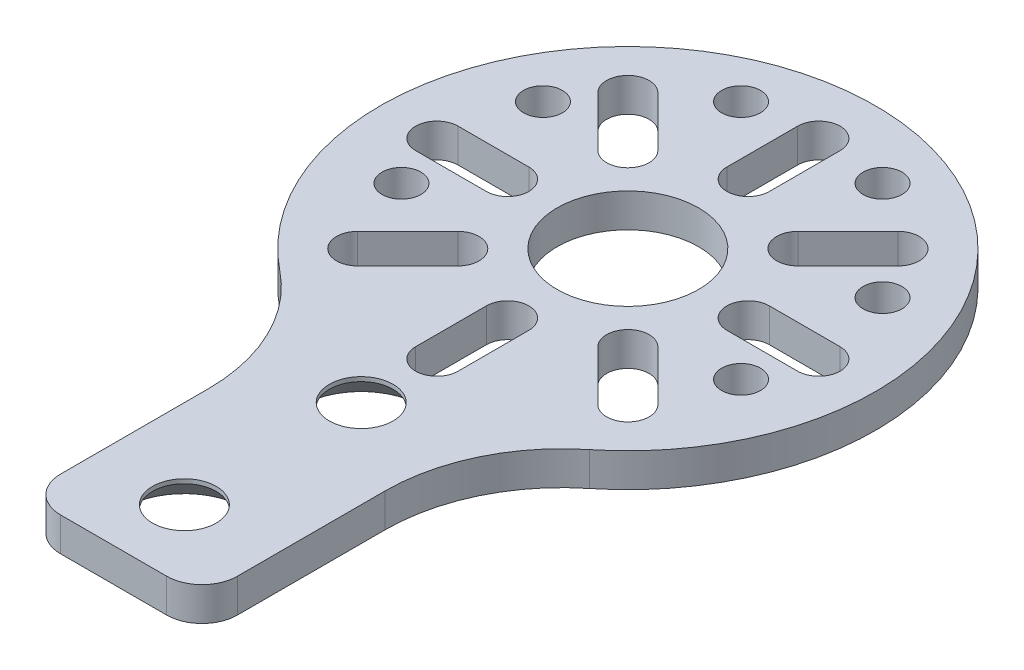
SolidWorks part; units mm, degrees
material "1060 Alloy"
ref_plane "Front Plane" through (0, 0, 0) normal (0, 0, 1) x (1, 0, 0)
ref_plane "Top Plane" through (0, 0, 0) normal (0, 1, 0) x (1, 0, 0)
ref_plane "Right Plane" through (0, 0, 0) normal (1, 0, 0) x (0, 0, -1)
sketch "Sketch1" plane through (0, 0, 0) normal (0, 1, 0) x (1, 0, 0)
  line L0 (-12.5, -72.6917) -> (12.5, -72.6917)
  line L1 (12.5, -72.6917) -> (12.5, -32.6917)
  line L2 (-12.5, -72.6917) -> (-12.5, -32.6917)
  arc A0 (12.5, -32.6917) -> (-12.5, -32.6917) centre (0, 0) ccw
  point P5 (0, -72.6917)
  dimension "D2" = 70
  dimension "D1" = 25
  dimension "D3" = 40
extrude "Boss-Extrude1" add sketch "Sketch1" along normal blind 4.7625 contours A0 L2 L0 L1
sketch "Sketch2" plane through (0, 0, 0) normal (0, -1, 0) x (1, 0, 0)
  line L0 (0, -2.6194) -> (0, 2.6194) construction
  point P0 (-10, -26)
  point P1 (-24, -12)
  point P4 (-24, 8)
  point P15 (24, 8)
  point P17 (24, -12)
  point P18 (10, -26)
  dimension "D2" = 26
  dimension "D1" = 8
  dimension "D3" = 10
  dimension "D4" = 24
  dimension "D5" = 20
sketch "Sketch5" plane through (0, 0, 0) normal (0, -1, 0) x (1, 0, 0)
  circle A0 centre (0, 0) radius 10
  dimension "D1" = 20
extrude "Cut-Extrude1" cut sketch "Sketch5" against normal through all
sketch "Sketch6" plane through (0, 0, 0) normal (0, -1, 0) x (1, 0, 0)
  line L0 (0, 72.6917) -> (0, 37.6917) construction
  line L1 (-12.5, 72.6917) -> (12.5, 72.6917) construction
  point P5 (0, 62.6917)
  dimension "D1" = 25
  dimension "D2" = 10
hole_wizard "CSK for M8 Flat Head Machine Screw1" positions "Sketch7" profile "Sketch8" countersink size "M8" standard "ANSI Metric" end condition through all
sketch "Sketch7" plane through (0, 0, 0) normal (0, -1, 0) x (-1, 0, 0)
  point P0 (0, -37.6917)
  point P3 (0, -62.6917)
sketch "Sketch8" plane through (0, 0, 37.6917) normal (1, 0, 0) x (0, 0, -1)
  line L0 (0, 0) -> (0, 4.7625)
  line L1 (0, 4.7625) -> (4.5, 4.7625)
  line L2 (4.5, 4.7625) -> (4.5, 4.15)
  line L3 (4.5, 4.15) -> (8.65, 0)
  line L5 (8.65, 0) -> (0, 0)
  line L6 (-4.5, 4.15) -> (-8.65, 0) construction
  line L11 (0, -6.35) -> (0, 107.95) construction
  dimension "Thru Hole Dia." = 9
  dimension "Thru Hole Depth" = 4.7625
  dimension "Near C'Sink Dia." = 17.3
  dimension "Near C'Sink Angle" = 90
fillet "Fillet1" radius 25 2 edges at (-12.5, 2.3813, 32.6917) (12.5, 2.3813, 32.6917)
hole_wizard "M5 Clearance Hole1" positions "Sketch9" profile "Sketch10" hole size "M5" standard "ANSI Metric" end condition through all
sketch "Sketch9" plane through (0, 0, 0) normal (0, -1, 0) x (-1, 0, 0)
  point P0 (10, 26)
  point P3 (24, 12)
  point P6 (24, -8)
  point P9 (-10, 26)
  point P12 (-24, 12)
  point P15 (-24, -8)
sketch "Sketch10" plane through (-10, 0, -26) normal (1, 0, 0) x (0, 0, -1)
  line L0 (0, 0) -> (0, 4.7625)
  line L1 (0, 4.7625) -> (2.75, 4.7625)
  line L2 (2.75, 4.7625) -> (2.75, 0.025)
  line L3 (2.75, 0.025) -> (2.775, 0)
  line L5 (2.775, 0) -> (0, 0)
  line L6 (-2.75, 0.025) -> (-2.775, 0) construction
  line L11 (0, -6.35) -> (0, 107.95) construction
  dimension "Thru Hole Dia." = 5.5
  dimension "Thru Hole Depth" = 4.7625
  dimension "Near C'Sink Dia." = 5.55
  dimension "Near C'Sink Angle" = 90
fillet "Fillet2" radius 5 2 edges at (-12.5, 2.3813, 72.6917) (12.5, 2.3813, 72.6917)
hole_wizard "M8 Clearance Hole1" positions "3DSketch1" profile "Sketch11" hole size "M8" standard "ANSI Metric"
sketch3d "3DSketch1"
  point P0 (0, 0, 37.6917)
  point P3 (0, 0, 62.6917)
sketch "Sketch11" plane through (0, 0, 37.6917) normal (1, 0, 0) x (0, 0, -1)
  line L0 (0, 0) -> (0, 4.7625)
  line L1 (0, 4.7625) -> (4.5, 4.7625)
  line L2 (4.5, 4.7625) -> (4.5, 0)
  line L5 (4.5, 0) -> (0, 0)
  line L11 (0, -6.35) -> (0, 107.95) construction
  dimension "Thru Hole Dia." = 9
  dimension "Thru Hole Depth" = 4.7625
sketch "Sketch12" plane through (0, 4.7625, 0) normal (0, 1, 0) x (1, 0, 0)
  line L0 (17, 0) -> (27, 0) construction
  line L1 (17, 3) -> (27, 3)
  line L2 (17, -3) -> (27, -3)
  line L3 (12.0208, -12.0208) -> (19.0919, -19.0919) construction
  line L4 (14.1421, -9.8995) -> (21.2132, -16.9706)
  line L5 (9.8995, -14.1421) -> (16.9706, -21.2132)
  line L6 (0, -17) -> (0, -27) construction
  line L7 (3, -17) -> (3, -27)
  line L8 (-3, -17) -> (-3, -27)
  line L9 (-12.0208, -12.0208) -> (-19.0919, -19.0919) construction
  line L10 (-9.8995, -14.1421) -> (-16.9706, -21.2132)
  line L11 (-14.1421, -9.8995) -> (-21.2132, -16.9706)
  line L12 (-17, 0) -> (-27, 0) construction
  line L13 (-17, -3) -> (-27, -3)
  line L14 (-17, 3) -> (-27, 3)
  line L15 (-12.0208, 12.0208) -> (-19.0919, 19.0919) construction
  line L16 (-14.1421, 9.8995) -> (-21.2132, 16.9706)
  line L17 (-9.8995, 14.1421) -> (-16.9706, 21.2132)
  line L18 (0, 17) -> (0, 27) construction
  line L19 (-3, 17) -> (-3, 27)
  line L20 (3, 17) -> (3, 27)
  line L21 (12.0208, 12.0208) -> (19.0919, 19.0919) construction
  line L22 (9.8995, 14.1421) -> (16.9706, 21.2132)
  line L23 (14.1421, 9.8995) -> (21.2132, 16.9706)
  arc A0 (17, 3) -> (17, -3) centre (17, 0) ccw
  arc A1 (27, -3) -> (27, 3) centre (27, 0) ccw
  arc A2 (14.1421, -9.8995) -> (9.8995, -14.1421) centre (12.0208, -12.0208) ccw
  arc A3 (16.9706, -21.2132) -> (21.2132, -16.9706) centre (19.0919, -19.0919) ccw
  arc A4 (3, -17) -> (-3, -17) centre (0, -17) ccw
  arc A5 (-3, -27) -> (3, -27) centre (0, -27) ccw
  arc A6 (-9.8995, -14.1421) -> (-14.1421, -9.8995) centre (-12.0208, -12.0208) ccw
  arc A7 (-21.2132, -16.9706) -> (-16.9706, -21.2132) centre (-19.0919, -19.0919) ccw
  arc A8 (-17, -3) -> (-17, 3) centre (-17, 0) ccw
  arc A9 (-27, 3) -> (-27, -3) centre (-27, 0) ccw
  arc A10 (-14.1421, 9.8995) -> (-9.8995, 14.1421) centre (-12.0208, 12.0208) ccw
  arc A11 (-16.9706, 21.2132) -> (-21.2132, 16.9706) centre (-19.0919, 19.0919) ccw
  arc A12 (-3, 17) -> (3, 17) centre (0, 17) ccw
  arc A13 (3, 27) -> (-3, 27) centre (0, 27) ccw
  arc A14 (9.8995, 14.1421) -> (14.1421, 9.8995) centre (12.0208, 12.0208) ccw
  arc A15 (21.2132, 16.9706) -> (16.9706, 21.2132) centre (19.0919, 19.0919) ccw
  circle A16 centre (0, 0) radius 10 construction
  arc A17 (21.875, -27.3219) -> (-21.875, -27.3219) centre (0, 0) ccw construction
  point P2 (22, 0)
  point P7 (9.6673, 17.5011)
  point P8 (0, 0)
  point P9 (0, 0)
  point P12 (15.5563, -15.5563)
  point P19 (0, -22)
  point P26 (-15.5563, -15.5563)
  point P31 (0, 0)
  point P33 (14.3541, 0)
  point P34 (26.6503, 0)
  point P37 (-22, 0)
  point P44 (-15.5563, 15.5563)
  point P51 (0, 22)
  point P58 (15.5563, 15.5563)
  point P63 (12.0292, 12.0292)
  dimension "D2" = 4
  dimension "D3" = 8
  dimension "D1" = 8
extrude "Cut-Extrude2" cut sketch "Sketch12" against normal through all
